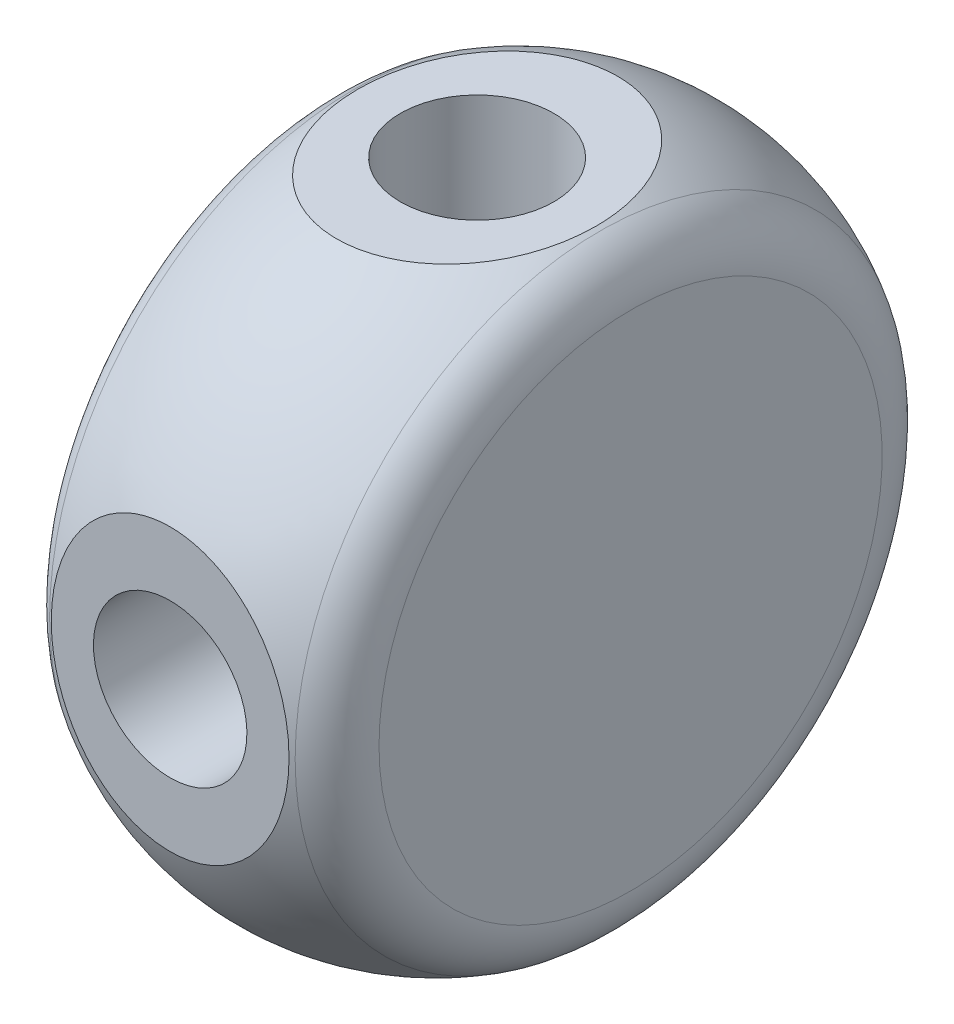
SolidWorks part; units mm, degrees
material "Brass"
ref_plane "Front Plane" through (0, 0, 0) normal (0, 0, 1) x (1, 0, 0)
ref_plane "Top Plane" through (0, 0, 0) normal (0, 1, 0) x (1, 0, 0)
ref_plane "Right Plane" through (0, 0, 0) normal (1, 0, 0) x (0, 0, -1)
sketch "Sketch1" plane through (0, 0, 0) normal (1, 0, 0) x (0, 0, -1)
  line L1 (-10, -10) -> (10, -10)
  line L2 (-10, -10) -> (-10, 10)
  line L3 (-10, 10) -> (10, 10)
  line L4 (10, -10) -> (10, 10)
  line L5 (-10, -10) -> (10, 10) construction
  line L6 (-10, 10) -> (10, -10) construction
  point P0 (0, 0)
  dimension "D1" = 20
extrude "Boss-Extrude1" add sketch "Sketch1" along normal mid plane 10
sketch "Sketch2" plane through (0, 10, 0) normal (0, 1, 0) x (1, 0, 0)
  circle A0 centre (0, 0) radius 3
  dimension "D1" = 6
ref_plane "Plane1" through (0, 0, 0) normal (0, 0.7071, 0.7071) x (1, 0, 0)
sketch "Sketch5" plane through (0, 0, 0) normal (0, 0.7071, 0.7071) x (1, 0, 0)
  line L0 (-5.7505, 0) -> (5.6873, 0) construction
  line L1 (-5, 14.1421) -> (-5, 0) construction
  line L2 (5, 14.1421) -> (5, 0) construction
  line L3 (-5, 9.245) -> (-5, 18.245)
  line L4 (-5, 18.245) -> (5, 18.245)
  line L5 (5, 18.245) -> (5, 9.245)
  arc A0 (-5, 9.245) -> (5, 9.245) centre (0, 3) cw
  dimension "D1" = 8
  dimension "D2" = 3
  dimension "D3" = 9
revolve "Cut-Revolve3" cut sketch "Sketch5" angle 360 about L0
hole_wizard "Tap Drill for M6 Tap1" positions "Sketch7" profile "Sketch8" hole size "M6" standard "IS"
sketch "Sketch7" plane through (0, 10, 0) normal (0, 1, 0) x (1, 0, 0)
  point P0 (0, 0)
sketch "Sketch8" plane through (0, 10, 0) normal (1, 0, 0) x (0, 0, 1)
  line L0 (0, 0) -> (0, 7.5022)
  line L1 (0, 7.5022) -> (2.5, 6)
  line L2 (2.5, 6) -> (2.5, 0)
  line L5 (2.5, 0) -> (0, 0)
  line L10 (0, 7.5022) -> (-2.5, 6) construction
  line L11 (0, -6.35) -> (0, 107.95) construction
  dimension "Hole Dia." = 5
  dimension "Hole Depth" = 6
  dimension "Drill Angle" = 118
pattern_circular "CirPattern1" count 4 over 360 of "Tap Drill for M6 Tap1"
fillet "Fillet1" radius 2 2 edges at (-5, 0, 9.245) (5, 0, 9.245)
